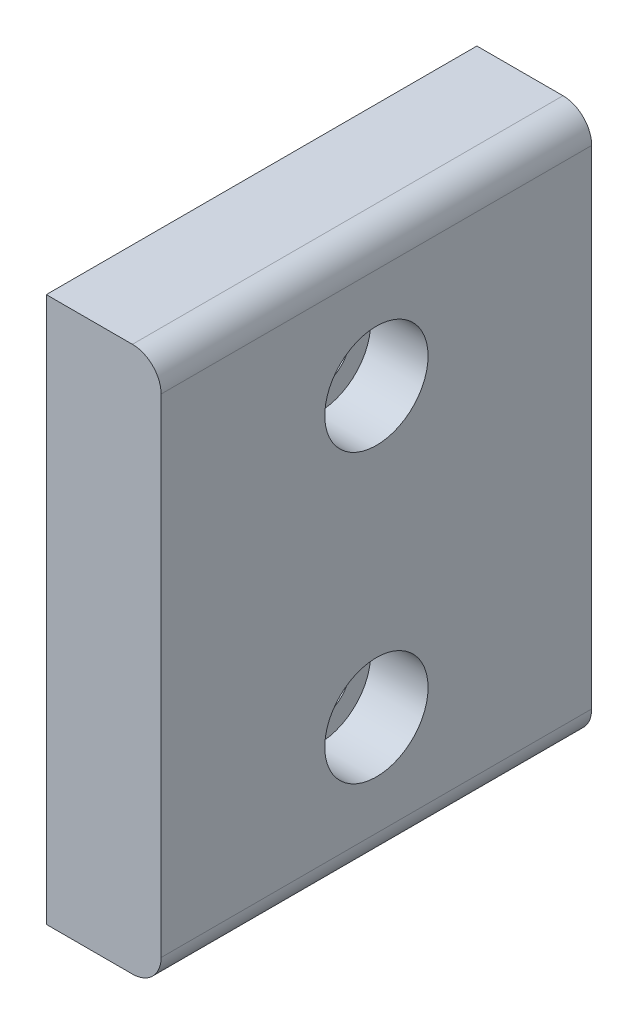
SolidWorks part; units mm, degrees
ref_plane "Спереди" through (0, 0, 0) normal (0, 0, 1) x (1, 0, 0)
ref_plane "Сверху" through (0, 0, 0) normal (0, 1, 0) x (1, 0, 0)
ref_plane "Справа" through (0, 0, 0) normal (1, 0, 0) x (0, 0, -1)
sketch "Эскиз1" plane through (0, 0, 0) normal (1, 0, 0) x (0, 0, -1)
  line L0 (-7.5, 0) -> (7.5, 0) construction
  line L1 (-7.5, 9.5) -> (7.5, 9.5)
  line L2 (-7.5, 9.5) -> (-7.5, -9.5)
  line L3 (-7.5, -9.5) -> (7.5, -9.5)
  line L4 (7.5, 9.5) -> (7.5, -9.5)
  line L5 (-7.5, 9.5) -> (7.5, -9.5) construction
  line L6 (-7.5, -9.5) -> (7.5, 9.5) construction
  circle A0 centre (0, 5) radius 1.1
  circle A1 centre (0, -5) radius 1.1
  point P0 (0, 0)
  dimension "D4" = 2.2
  dimension "D1" = 19
  dimension "D2" = 15
  dimension "D3" = 10
extrude "Бобышка-Вытянуть1" add sketch "Эскиз1" along normal blind 4
sketch "Эскиз2" plane through (4, 0, 0) normal (1, 0, 0) x (0, 0, -1)
  circle A0 centre (0, 5) radius 1.8
  circle A1 centre (0, -5) radius 1.8
  dimension "D1" = 3.6
  dimension "D2" = 3.6
extrude "Вырез-Вытянуть1" cut sketch "Эскиз2" against normal blind 2
fillet "Скругление1" radius 1 2 edges at (4, -9.5, 0) (4, 9.5, 0)
equation "\"motor_diameter\"= 30"
equation "\"mm_diameter\"= IIF ( \"motor_diameter\" < 34 , 41 , \"motor_diameter\" + 8 )"
equation "\"upper_shafts_diameter\"= 5"
equation "\"upper_shats_length\"= 180"
equation "\"upper_bearing_d1\"= 10"
equation "\"upper_bearing_d2\"= 5"
equation "\"upper_bearing_h\"= 15"
equation "\"lower_shafts_diameter\"= 5"
equation "\"lower_shafts_length\"= 180"
equation "\"lower_bearing_d1\"= 10"
equation "\"lower_bearing_d2\"= 5"
equation "\"lower_bearing_h\"= 15"
equation "\"print_offset\"= 0.2"
equation "\"bh_screws_d\"= 2"
equation "\"bh_screws_h\"= 20"
equation "\"bh_screws_hh_d\"= 3.4"
equation "\"bh_screws_hh_h\"= 2"
equation "\"bh_nut_d\"= 3.8"
equation "\"bh_nut_h\"= 2"
equation "\"motor_screws_d\"= 3"
equation "\"motor_screws_h\"= 16"
equation "\"motor_screws_hh_d\"= 5.5"
equation "\"motor_screws_hh_h\"= 3"
equation "\"plate_hole_distance\"= 25.4"
equation "\"plate_screws_d\"= 6.5"
equation "\"shafts_diameter\"= IIF ( \"mm_diameter\" < 42 , 42 + 8 , \"mm_diameter\" + 8 )"
equation "\"central_hole_diameter\"= 8"
equation "\"bh_thikness\"= 4"
equation "\"ends_screws_d\"= 4"
equation "\"ends_screws_h\"= 16"
equation "\"ends_screws_hh_d\"= 6.7"
equation "\"ends_screws_hh_h\"= 4.1"
equation "\"ends_nut_d\"= 6.8"
equation "\"ends_nut_h\"= 3"
equation "\"system_radius\" = ( \"shafts_diameter\" + 12 + \"bh_thikness\" / 2 ) / 2"
equation "\"encoder_distance\"= \"system_radius\" + 4"
equation "\"tape_position\"= \"encoder_distance\" - 2 + 3.9 + 1.7 / 2"
equation "\"D1@Эскиз1\"=\"upper_bearing_h\" + 6 + 3 - 8 + 3"
equation "\"D4@Эскиз1\"=\"bh_screws_d\"+\"print_offset\""
equation "\"D1@Эскиз2\"=\"bh_screws_hh_d\"+\"print_offset\""
equation "\"D2@Эскиз2\"=\"D1@Эскиз2\""
